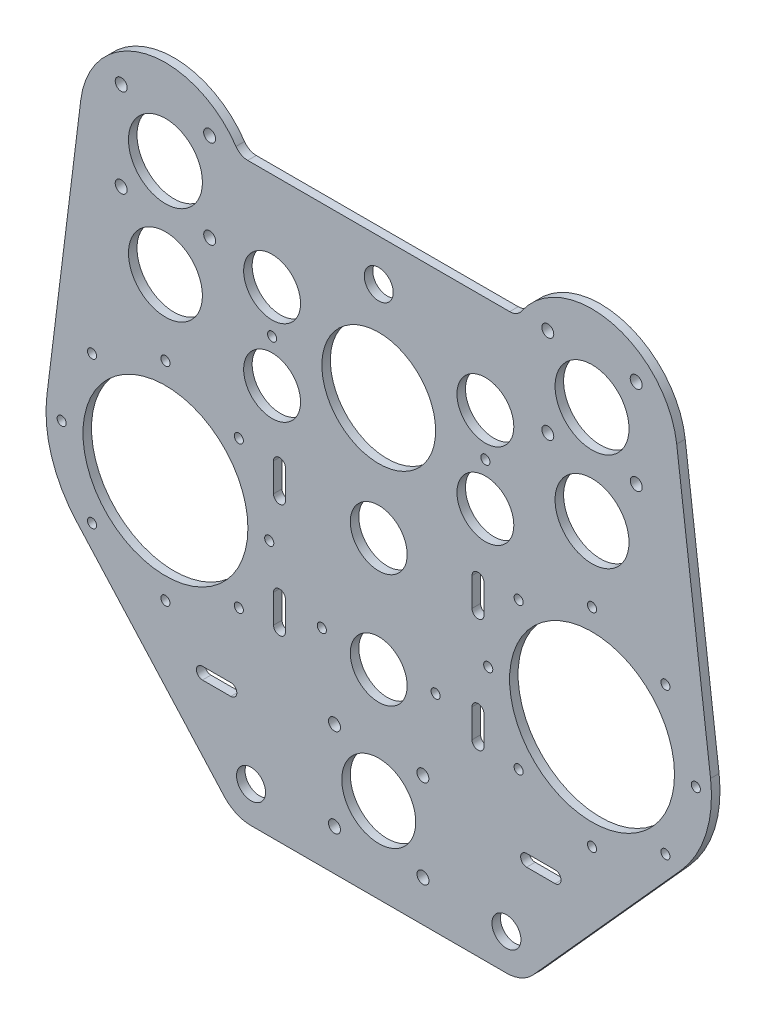
SolidWorks part; units mm, degrees
material "Thornel Mat VMA"
ref_plane "Front Plane" through (0, 0, 0) normal (0, 0, 1) x (1, 0, 0)
ref_plane "Top Plane" through (0, 0, 0) normal (0, 1, 0) x (1, 0, 0)
ref_plane "Right Plane" through (0, 0, 0) normal (1, 0, 0) x (0, 0, -1)
sketch "Model" plane through (0, 0, 0) normal (0, 0, 1) x (1, 0, 0)
  line L0 (-37, 5) -> (-37, -5)
  line L1 (-32.8, 5) -> (-32.8, -5)
  line L2 (-37, -35) -> (-37, -45)
  line L3 (-32.8, -35) -> (-32.8, -45)
  line L4 (-44.9, -110) -> (0, -110)
  line L5 (37, 5) -> (37, -5)
  line L6 (32.8, 5) -> (32.8, -5)
  line L7 (37, -35) -> (37, -45)
  line L8 (32.8, -35) -> (32.8, -45)
  line L9 (44.9, -110) -> (0, -110)
  line L10 (-62, -70) -> (-52, -70)
  line L11 (-62, -74.2) -> (-52, -74.2)
  line L12 (62, -70) -> (52, -70)
  line L13 (62, -74.2) -> (52, -74.2)
  line L14 (-106.2292, -48.0845) -> (-54.3252, -105.8002)
  line L15 (106.2292, -48.0845) -> (54.3252, -105.8002)
  line L16 (-46.0542, 92) -> (0, 92)
  line L17 (46.0542, 92) -> (0, 92)
  line L18 (-104.7711, 81.0231) -> (-116.6795, -14.8214)
  line L19 (104.7711, 81.0231) -> (116.6795, -14.8214)
  circle A0 centre (0, -80) radius 13
  arc A1 (-32.8, 5) -> (-37, 5) centre (-34.9, 5) ccw
  arc A2 (-37, -5) -> (-32.8, -5) centre (-34.9, -5) ccw
  arc A3 (-32.8, -35) -> (-37, -35) centre (-34.9, -35) ccw
  arc A4 (-37, -45) -> (-32.8, -45) centre (-34.9, -45) ccw
  circle A5 centre (-44.9, -97.3241) radius 5.1
  arc A6 (37, 5) -> (32.8, 5) centre (34.9, 5) ccw
  arc A7 (32.8, -5) -> (37, -5) centre (34.9, -5) ccw
  arc A8 (37, -35) -> (32.8, -35) centre (34.9, -35) ccw
  arc A9 (32.8, -45) -> (37, -45) centre (34.9, -45) ccw
  circle A10 centre (44.9, -97.3241) radius 5.1
  arc A11 (-62, -70) -> (-62, -74.2) centre (-62, -72.1) ccw
  arc A12 (-52, -74.2) -> (-52, -70) centre (-52, -72.1) ccw
  arc A13 (62, -74.2) -> (62, -70) centre (62, -72.1) ccw
  arc A14 (52, -70) -> (52, -74.2) centre (52, -72.1) ccw
  circle A15 centre (0, 77.3241) radius 5.1
  circle A16 centre (0, 0) radius 10
  circle A17 centre (0, -40) radius 10
  circle A18 centre (0, 42.6759) radius 20
  circle A19 centre (-37.5, 57.6759) radius 10
  circle A20 centre (-37.5, 27.6759) radius 10
  circle A21 centre (37.5, 57.6759) radius 10
  circle A22 centre (37.5, 27.6759) radius 10
  arc A23 (-54.3252, -105.8002) -> (-44.9, -110) centre (-44.9, -97.3241) ccw
  arc A24 (44.9, -110) -> (54.3252, -105.8002) centre (44.9, -97.3241) ccw
  circle A25 centre (-75, -20) radius 29
  circle A26 centre (-75, 16.5) radius 1.6
  circle A27 centre (-100.8094, 5.8094) radius 1.6
  circle A28 centre (-49.1906, 5.8094) radius 1.6
  circle A29 centre (-38.5, -20) radius 1.6
  circle A30 centre (-49.1906, -45.8094) radius 1.6
  circle A31 centre (-75, -56.5) radius 1.6
  circle A32 centre (-100.8094, -45.8094) radius 1.6
  circle A33 centre (-111.5, -20) radius 1.6
  circle A34 centre (75, -20) radius 29
  circle A35 centre (75, 16.5) radius 1.6
  circle A36 centre (49.1906, 5.8094) radius 1.6
  circle A37 centre (100.8094, 5.8094) radius 1.6
  circle A38 centre (111.5, -20) radius 1.6
  circle A39 centre (100.8094, -45.8094) radius 1.6
  circle A40 centre (75, -56.5) radius 1.6
  circle A41 centre (49.1906, -45.8094) radius 1.6
  circle A42 centre (38.5, -20) radius 1.6
  circle A43 centre (-75, 77.3241) radius 13
  arc A44 (-50.1893, 94.1892) -> (-104.7711, 81.0231) centre (-75, 77.3241) ccw
  arc A45 (-50.1893, 94.1892) -> (-46.0542, 92) centre (-46.0542, 97) ccw
  circle A46 centre (75, 77.3241) radius 13
  arc A47 (104.7711, 81.0231) -> (50.1893, 94.1892) centre (75, 77.3241) ccw
  arc A48 (46.0542, 92) -> (50.1893, 94.1892) centre (46.0542, 97) ccw
  arc A49 (-116.6795, -14.8214) -> (-106.2292, -48.0845) centre (-75, -20) ccw
  arc A50 (106.2292, -48.0845) -> (116.6795, -14.8214) centre (75, -20) ccw
  circle A51 centre (-75, 42.8013) radius 13
  circle A52 centre (75, 42.6759) radius 13
  circle A53 centre (-59.4676, 92.8565) radius 2.1
  circle A54 centre (-90.5563, 92.8805) radius 2.1
  circle A55 centre (-90.5563, 61.7678) radius 2.1
  circle A56 centre (-59.4437, 61.7678) radius 2.1
  circle A57 centre (90.5324, 92.8565) radius 2.1
  circle A58 centre (59.4437, 92.8805) radius 2.1
  circle A59 centre (59.4437, 61.7678) radius 2.1
  circle A60 centre (90.5563, 61.7678) radius 2.1
  circle A61 centre (15.5324, -64.4676) radius 2.1
  circle A62 centre (-15.5563, -64.4437) radius 2.1
  circle A63 centre (-15.5563, -95.5563) radius 2.1
  circle A64 centre (15.5563, -95.5563) radius 2.1
extrude "Boss-Extrude1" add sketch "Model" along normal blind 3
sketch "Sketch1" plane through (0, 0, 3) normal (0, 0, 1) x (1, 0, 0)
  line L0 (-37.5, 42.6759) -> (37.5, 42.6759) construction
  line L1 (-20, -37.3241) -> (20, -37.3241) construction
  line L2 (-37.5, 47.6759) -> (-37.5, 37.6759) construction
  circle A0 centre (-37.5, 42.6759) radius 1.6
  circle A1 centre (37.5, 42.6759) radius 1.6
  circle A2 centre (-20, -37.3241) radius 1.6
  circle A3 centre (20, -37.3241) radius 1.6
  circle A4 centre (-37.5, 57.6759) radius 10 construction
  circle A5 centre (-37.5, 27.6759) radius 10 construction
  point P8 (0, 42.6759)
  point P9 (0, -37.3241)
  point P18 (0, 0)
  point P19 (0, 0)
  point P20 (-37.5, 42.6759)
  dimension "D4" = 3.2
  dimension "D1" = 75
  dimension "D2" = 40
  dimension "D3" = 80
extrude "Cut-Extrude1" cut sketch "Sketch1" against normal up to next
